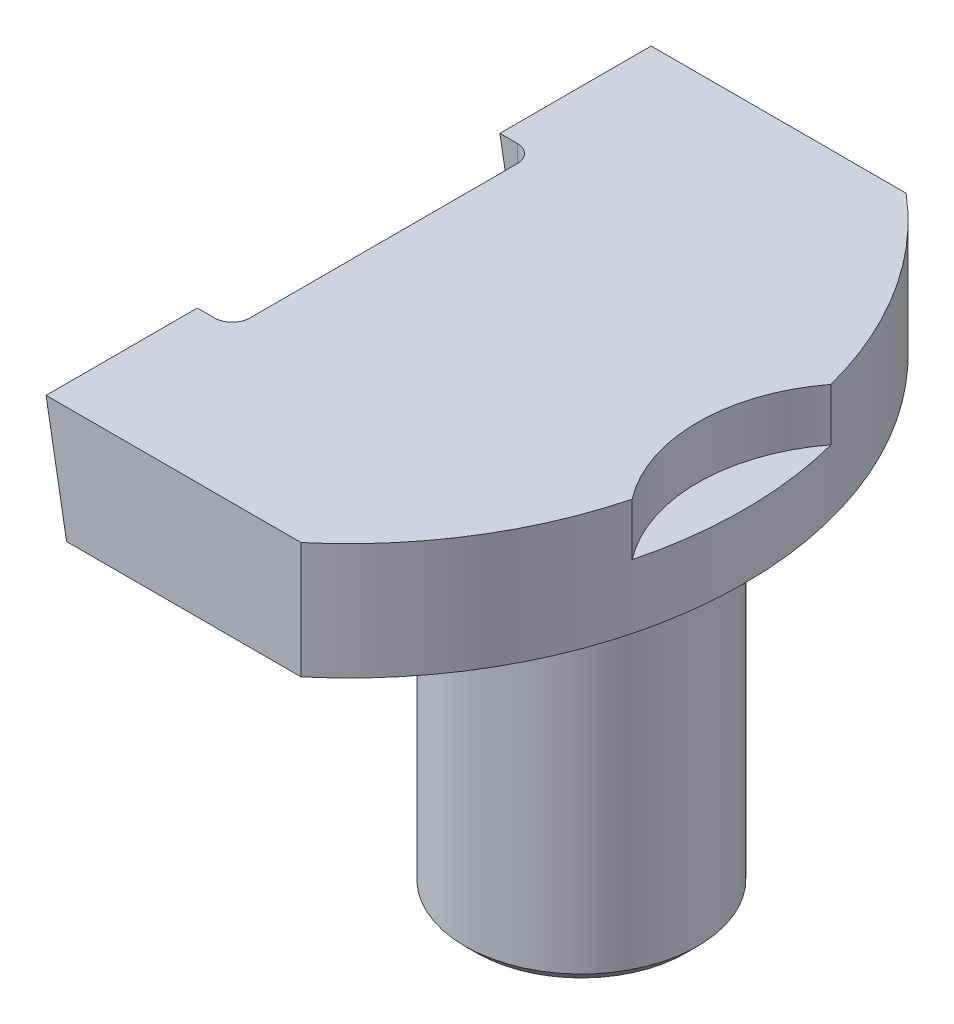
SolidWorks part; units mm, degrees
ref_plane "前视基准面" through (0, 0, 0) normal (0, 0, 1) x (1, 0, 0)
ref_plane "上视基准面" through (0, 0, 0) normal (0, 1, 0) x (1, 0, 0)
ref_plane "右视基准面" through (0, 0, 0) normal (1, 0, 0) x (0, 0, -1)
sketch "草图1" plane through (0, 0, 0) normal (0, 1, 0) x (1, 0, 0)
  circle A0 centre (0, 0) radius 10
  dimension "D1" = 20
extrude "凸台-拉伸1" add sketch "草图1" along normal blind 40
chamfer "倒角1" distance 1 angle 45 1 edges at (0, 0, 10)
sketch "草图2" plane through (0, 40, 0) normal (0, 1, 0) x (1, 0, 0)
  line L0 (-17, -13) -> (-17, 13)
  line L1 (-11, 0) -> (11, 0) construction
  line L2 (-17, 13) -> (-20, 13)
  line L3 (-20, 13) -> (-20, 26)
  line L4 (-20, 26) -> (1.9089, 26)
  line L5 (-17, 0) -> (9.7193, 0) construction
  line L6 (-20, -26) -> (1.9089, -26)
  line L7 (-20, -13) -> (-20, -26)
  line L8 (-17, -13) -> (-20, -13)
  arc A0 (1.9089, 26) -> (1.9089, -26) centre (-20, 0) cw
  dimension "D1" = 34
  dimension "D2" = 17
  dimension "D3" = 3
  dimension "D4" = 52
  dimension "D5" = 26
  dimension "D6" = 34
extrude "凸台-拉伸2" add sketch "草图2" against normal blind 10
sketch "草图3" plane through (0, 40, 0) normal (0, 1, 0) x (1, 0, 0)
  line L0 (0, -22) -> (0, 22) construction
  line L1 (-18.7, 0) -> (18.7, 0) construction
  circle A0 centre (24, 0) radius 14
  point P4 (0, 0)
  dimension "D1" = 28
  dimension "D2" = 24
extrude "切除-拉伸1" cut sketch "草图3" against normal blind 4.5
sketch "草图4" plane through (0, 0, 26) normal (0, 0, 1) x (1, 0, 0)
  line L0 (-20, 40) -> (-18.2367, 30)
  line L1 (-20, 30) -> (1.9089, 30) construction
  line L2 (-20, 30) -> (-20, 40) construction
  dimension "D1" = 10
extrude "切除-拉伸2" cut sketch "草图4" against normal through all and the other way through all flip side to cut
sketch "草图5" plane through (0, 30, 0) normal (0, -1, 0) x (1, 0, 0)
  circle A2 centre (0, 0) radius 9.5
  circle A3 centre (0, 0) radius 9.5
  dimension "D1" = 0.5
extrude "切除-拉伸3" cut sketch "草图5" along normal blind 2 flip side to cut
fillet "圆角1" radius 1.5 2 edges at (-17, 35, 13) (-17, 35, -13)
